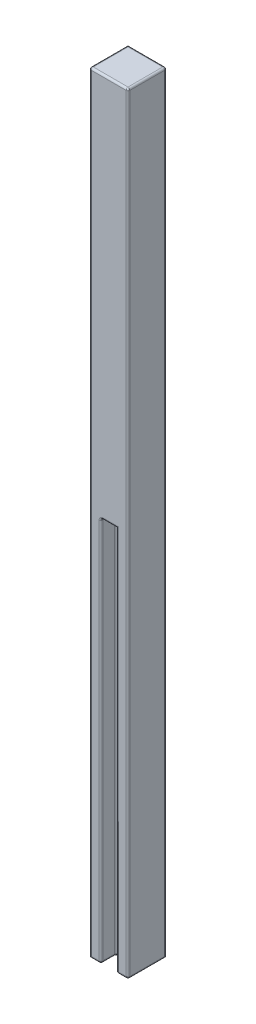
SolidWorks part; units mm, degrees
ref_plane "Front Plane" through (0, 0, 0) normal (0, 0, 1) x (1, 0, 0)
ref_plane "Top Plane" through (0, 0, 0) normal (0, 1, 0) x (1, 0, 0)
ref_plane "Right Plane" through (0, 0, 0) normal (1, 0, 0) x (0, 0, -1)
sketch "Sketch1" plane through (0, 0, 0) normal (0, 1, 0) x (1, 0, 0)
  line L1 (-43.4919, 32.6944) -> (-33.4919, 32.6944)
  line L2 (-43.4919, 32.6944) -> (-43.4919, 22.6944)
  line L3 (-43.4919, 22.6944) -> (-33.4919, 22.6944)
  line L4 (-33.4919, 32.6944) -> (-33.4919, 22.6944)
  dimension "D2" = 10
extrude "Boss-Extrude1" add sketch "Sketch1" along normal blind 200
sketch "Sketch2" plane through (0, 0, -22.6944) normal (0, 0, 1) x (1, 0, 0)
  line L0 (-43.4919, 200) -> (-43.4919, 0) construction
  line L1 (-40.4919, 100) -> (-36.4919, 100)
  line L2 (-40.4919, 100) -> (-40.4919, 0)
  line L3 (-40.4919, 0) -> (-36.4919, 0)
  line L4 (-36.4919, 100) -> (-36.4919, 0)
  line L5 (-43.4919, 0) -> (-33.4919, 0) construction
  dimension "D1" = 100
  dimension "D2" = 4
  dimension "D3" = 3
  dimension "D4" = 0
extrude "Cut-Extrude1" cut sketch "Sketch2" against normal blind 4 contours L1 L4 L3 L2
fillet "Fillet1" radius 0.5 20 edges at (-36.4919, 0, -24.6944) (-40.4919, 50, -22.6944) (-36.4919, 50, -22.6944) (-38.4919, 100, -22.6944) (-40.4919, 50, -26.6944) (-38.4919, 0, -26.6944) (-36.4919, 50, -26.6944) (-38.4919, 100, -26.6944) (-40.4919, 0, -24.6944) (-40.4919, 100, -24.6944) (-34.9919, 0, -22.6944) (-41.9919, 0, -22.6944) (-33.4919, 0, -27.6944) (-43.4919, 200, -27.6944) (-38.4919, 200, -22.6944) (-33.4919, 200, -27.6944) (-38.4919, 200, -32.6944) (-33.4919, 100, -32.6944) (-33.4919, 100, -22.6944) (-43.4919, 100, -22.6944)
equation "\"BeamWidth\" = 10"
equation "\"BeamLength\" = 10"
equation "\"BeamHeight\" = 200"
equation "\"D1@Sketch1\"=\"BeamWidth\""
equation "\"D2@Sketch1\"=\"BeamLength\""
equation "\"D1@Boss-Extrude1\"=\"BeamHeight\""
equation "\"LegHeight\" = 100"
equation "\"LegScannerWidth\" = 4"
equation "\"D1@Sketch2\"=\"LegHeight\""
equation "\"D2@Sketch2\"=\"LegScannerWidth\""
equation "\"D3@Sketch2\"=(\"BeamWidth\"-\"LegScannerWidth\")/2"
equation "\"LegScannerDepth\" = 4"
equation "\"D1@Cut-Extrude1\"=\"LegScannerDepth\""
